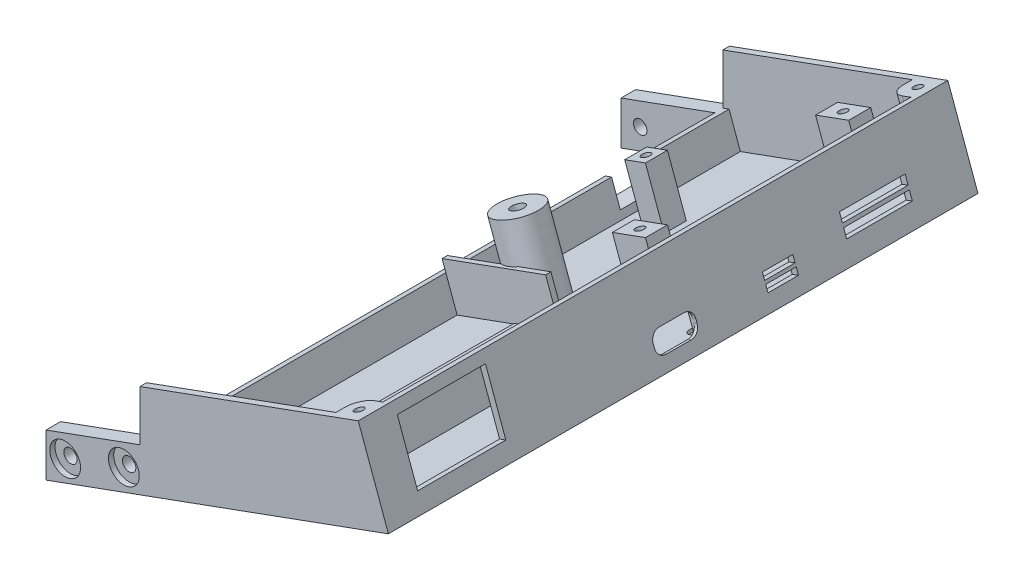
SolidWorks part; units mm, degrees
ref_plane "Front Plane" through (0, 0, 0) normal (0, 0, 1) x (1, 0, 0)
ref_plane "Top Plane" through (0, 0, 0) normal (0, 1, 0) x (1, 0, 0)
ref_plane "Right Plane" through (0, 0, 0) normal (1, 0, 0) x (0, 0, -1)
sketch "Sketch1" plane through (0, 0, 0) normal (0, 0, 1) x (1, 0, 0)
  line L1 (-6.3114, -55.8912) -> (15, -48.1345) construction
  line L2 (-6.1614, -45.8912) -> (-6.1614, -55.8912)
  line L3 (-6.1614, -45.8912) -> (-6.1614, -55.8912)
  line L4 (-6.3114, -55.8912) -> (15, -48.1345)
  line L6 (15, -48.1345) -> (15, -38.1345) construction
  line L7 (15.0513, -38.2754) -> (-6.2601, -46.0321)
  line L8 (15.0513, -38.2754) -> (-6.2601, -46.0321)
  line L9 (15, -48.1345) -> (15, -38.1345) construction
  line L10 (15, -48.1345) -> (15.141, -48.0832)
  line L11 (15.141, -48.0832) -> (15.141, -38.2428)
  line L12 (15.141, -38.2428) -> (15.0513, -38.2754)
  circle A0 centre (11.5, -44.4591) radius 1.525 construction
  circle A1 centre (11.5, -44.4591) radius 1.525
  circle A2 centre (-1.8114, -49.4969) radius 1.525 construction
  circle A3 centre (-1.8114, -49.4969) radius 1.525
  point P4 (90.4357, -10.8378)
  point P9 (16.5754, -48.1345)
  dimension "D3" = 0.15
  dimension "D1" = 0.15
  dimension "D2" = 0.15
extrude "Boss-Extrude1" add sketch "Sketch1" along normal blind 3.5 contours L9 L10 L11 L12 L8 | L4 L9 L8 L3 A3 A1
sketch "Sketch2" plane through (0, 0, 0) normal (0, 0, -1) x (-1, 0, 0)
  line L4 (6.1614, -45.9962) -> (-15.141, -38.2428)
  line L5 (-15.141, -38.2428) -> (-15.141, -48.0832)
  line L6 (-15.141, -48.0832) -> (6.1614, -55.8366)
  line L8 (6.1614, -45.9962) -> (-15.141, -38.2428)
  line L9 (-15.141, -38.2428) -> (-15.141, -48.0832)
  line L12 (-15.141, -48.0832) -> (6.1614, -55.8366)
  line L14 (6.1614, -55.8366) -> (6.1614, -45.9962)
  line L15 (6.1614, -55.8366) -> (6.1614, -45.9962)
  dimension "D1" = 0
extrude "Cut-Extrude1" cut sketch "Sketch2" against normal blind 0.2
ref_plane "Plane1" through (0, 0, -63.3801) normal (0, 0, 1) x (1, 0, 0)
mirror "Mirror2" about plane through (0, 0, -63.3801) normal (0, 0, 1) of bodies 102
sketch "Sketch3" plane through (0, 0, 3.5) normal (0, 0, 1) x (1, 0, 0)
  line L0 (15.141, -48.0832) -> (15.141, -38.2428) construction
  line L1 (15.141, -48.0832) -> (15.141, -38.2428)
  line L2 (15.141, -48.0832) -> (71.5225, -27.562)
  line L3 (71.5225, -27.562) -> (68.3599, -18.8727)
  line L4 (68.3599, -18.8727) -> (15.141, -38.2428)
  line L5 (15, -38.1345) -> (-6.3114, -45.8912) construction
  line L6 (-6.1614, -55.8366) -> (15.141, -48.0832) construction
  dimension "D1" = 60
extrude "Boss-Extrude2" add sketch "Sketch3" against normal up to surface (133.7602 mm away) up to face at (4.4898, -47.0397, -130.2602)
sketch "Sketch4" plane through (14.0622, -38.6354, 0) normal (-0.342, 0.9397, 0) x (0.9397, 0.342, 0)
  line L2 (56.2824, 130.2602) -> (56.2824, -3.5)
  line L3 (56.2824, 130.2602) -> (56.2824, -3.5)
  line L5 (57.7824, 128.7602) -> (-21.5215, 128.7602)
  line L6 (57.7824, 128.7602) -> (-21.5215, 128.7602)
  line L8 (57.7824, -2) -> (-21.5215, -2)
  line L9 (57.7824, -2) -> (-21.5215, -2)
  line L11 (2.648, 126.9602) -> (2.648, -0.2)
  line L12 (2.648, 128.7602) -> (2.648, -2)
  point P0 (2.6045, -2)
  dimension "D1" = 1.5
  dimension "D2" = 1.5
  dimension "D3" = 1.5
  dimension "D4" = 1.5
extrude "Cut-Extrude2" cut sketch "Sketch4" against normal blind 7.5 contours L6 L12 L9 L3
sketch "Sketch5" plane through (0, 0, 3.5) normal (0, 0, 1) x (1, 0, 0)
  line L1 (68.3599, -18.8727) -> (-6.1614, -45.9962) construction
  line L2 (15.15, 39.2) -> (15.15, -38.1345)
  line L3 (15.15, 39.2) -> (15.15, -74.4086)
  line L4 (68.3599, -18.8727) -> (-6.1614, -45.9962)
  line L5 (71.5225, -27.562) -> (68.3599, -18.8727) construction
  line L6 (71.5225, -27.562) -> (68.3599, -18.8727)
  line L7 (15.15, -26.7963) -> (64.6821, -8.7681)
  line L8 (64.6821, -8.7681) -> (68.3599, -18.8727)
  line L9 (-6.1614, -55.8366) -> (71.5225, -27.562) construction
  line M6 (68.3599, -18.8727) -> (-6.1614, -45.9962)
  dimension "D2" = 20
  dimension "D1" = 0.15
extrude "Boss-Extrude3" add sketch "Sketch5" against normal up to surface (1.5 mm away) contours L8 L7 L3 M6 up to face at (43.033, -32.0816, 2)
sketch "Sketch6" plane through (0, 0, -130.2602) normal (0, 0, -1) x (-1, 0, 0)
  line L0 (-15.15, -26.7963) -> (-64.6821, -8.7681) construction
  line L1 (-64.6821, -8.7681) -> (-68.3599, -18.8727) construction
  line L2 (-71.5225, -27.562) -> (-68.3599, -18.8727) construction
  line L3 (-68.3599, -18.8727) -> (6.1614, -45.9962) construction
  line L4 (-15.15, 39.2) -> (-15.15, -74.4086) construction
  line L5 (-15.15, -26.7963) -> (-64.6821, -8.7681)
  line L6 (-64.6821, -8.7681) -> (-68.3599, -18.8727)
  line L7 (-71.5225, -27.562) -> (-68.3599, -18.8727)
  line L8 (-68.3599, -18.8727) -> (6.1614, -45.9962)
  line L9 (-15.15, 39.2) -> (-15.15, -74.4086)
extrude "Boss-Extrude4" add sketch "Sketch6" against normal up to surface (1.5 mm away) contours L9 L5 L6 L8 up to face at (43.033, -32.0816, -128.7602)
sketch "Sketch7" plane through (54.2977, 19.7628, 0) normal (0.9397, 0.342, 0) x (0, 0, -1)
  line L0 (128.7602, -41.115) -> (-2, -41.115) construction
  line L1 (128.7602, -41.115) -> (-2, -41.115)
  line L2 (-2, -30.3619) -> (-2, -41.115) construction
  line L3 (-2, -30.3619) -> (-2, -41.115)
  line L4 (128.7602, -41.115) -> (128.7602, -30.3619) construction
  line L5 (128.7602, -41.115) -> (128.7602, -30.3619)
  line L6 (-2, -30.3619) -> (128.7602, -30.3619)
extrude "Boss-Extrude5" add sketch "Sketch7" against normal up to surface (1.5 mm away) up to face at (68.2329, -22.9096, -63.3801)
sketch "Sketch8" plane through (15.141, 0, 0) normal (-1, 0, 0) x (0, 0, 1)
  line L0 (-102.1, -43.2) -> (-113.1, -43.2) construction
  line L1 (-102.1, -43.2) -> (-113.1, -43.2)
  line L2 (-113.1, -52.7) -> (-113.1, -40.2) construction
  line L3 (-113.1, -52.7) -> (-113.1, -38.2428)
  line L4 (-102.1, -52.7) -> (-102.1, -40.2) construction
  line L5 (-102.1, -52.7) -> (-102.1, -38.2428)
  line L6 (-126.9602, -38.2428) -> (0.2, -38.2428) construction
  line L7 (-113.1, -38.2428) -> (-113.1, -35.0272)
  line L8 (-113.1, -35.0272) -> (-102.1, -35.0272)
  line L9 (-102.1, -35.0272) -> (-102.1, -38.2428)
  line M4 (0.2, -38.2428) -> (-126.9602, -38.2428)
extrude "Cut-Extrude3" cut sketch "Sketch8" against normal blind 5 contours L1 L5 L3 M4 | L9 L8 L7 M4
sketch "Sketch9" plane through (16.6273, -45.6831, 0) normal (-0.342, 0.9397, 0) x (0.9397, 0.342, 0)
  circle A0 centre (53.1824, 55.3801) radius 1.65 construction
  circle A1 centre (53.1824, 55.3801) radius 1.65
  circle A2 centre (53.1824, 71.3801) radius 1.65 construction
  circle A3 centre (53.1824, 71.3801) radius 1.65
extrude "Cut-Extrude4" cut sketch "Sketch9" against normal blind 1.8
sketch "Sketch10" plane through (16.6273, -45.6831, 0) normal (-0.342, 0.9397, 0) x (0.9397, 0.342, 0)
  line L2 (49.4824, 60.5301) -> (49.4824, 58.9301) construction
  line L5 (49.4824, 60.5301) -> (49.4824, 58.9301) construction
  line L6 (49.4824, 67.8301) -> (49.4824, 66.2301) construction
  line L7 (49.4824, 67.8301) -> (49.4824, 66.2301) construction
  line L8 (55.6824, 66.2301) -> (55.6824, 74.2801) construction
  line L9 (55.6824, 68.2301) -> (56.9824, 68.2301)
  line L10 (55.6824, 68.2301) -> (55.6824, 58.5301)
  line L11 (55.6824, 58.5301) -> (56.9824, 58.5301)
  line L12 (56.9824, 68.2301) -> (56.9824, 58.5301)
  dimension "D1" = 0.4
  dimension "D2" = 0.4
  dimension "D3" = 1.3
extrude "Cut-Extrude5" cut sketch "Sketch10" along normal blind 6
sketch "Sketch11" plane through (54.2977, 19.7628, 0) normal (0.9397, 0.342, 0) x (0, 0, -1)
  line L4 (66.2301, -43.415) -> (60.5301, -43.415)
  line L5 (60.5301, -47.415) -> (66.2301, -47.415)
  line L6 (66.2301, -43.415) -> (60.5301, -43.415)
  line L7 (60.5301, -47.415) -> (66.2301, -47.415)
  spline S0 degree 3 poles (60.5301, -43.415) (56.5301, -43.415) (56.5301, -47.415) (60.5301, -47.415) knots 0 0 0 0 1 1 1 1 weights 1 0.333333 0.333333 1
  spline S1 degree 3 poles (60.5301, -43.415) (56.5301, -43.415) (56.5301, -47.415) (60.5301, -47.415) knots 0 0 0 0 1 1 1 1 weights 1 0.333333 0.333333 1
  spline S2 degree 3 poles (66.2301, -47.415) (70.2301, -47.415) (70.2301, -43.415) (66.2301, -43.415) knots 0 0 0 0 1 1 1 1 weights 1 0.333333 0.333333 1
  spline S3 degree 3 poles (66.2301, -47.415) (70.2301, -47.415) (70.2301, -43.415) (66.2301, -43.415) knots 0 0 0 0 1 1 1 1 weights 1 0.333333 0.333333 1
  dimension "D1" = 0.4
extrude "Cut-Extrude6" cut sketch "Sketch11" against normal blind 6
sketch "Sketch12" plane through (54.2977, 19.7628, 0) normal (0.9397, 0.342, 0) x (0, 0, -1)
  line L8 (102.0602, -40.915) -> (102.0602, -42.915)
  line L9 (102.0602, -42.915) -> (116.9602, -42.915)
  line L10 (116.9602, -42.915) -> (116.9602, -40.915)
  line L11 (116.9602, -40.915) -> (102.0602, -40.915)
  line L12 (102.0602, -40.915) -> (102.0602, -42.915)
  line L13 (102.0602, -42.915) -> (116.9602, -42.915)
  line L14 (116.9602, -42.915) -> (116.9602, -40.915)
  line L15 (116.9602, -40.915) -> (102.0602, -40.915)
  line L20 (102.0602, -43.715) -> (102.0602, -45.715)
  line L21 (102.0602, -45.715) -> (116.9602, -45.715)
  line L22 (116.9602, -45.715) -> (116.9602, -43.715)
  line L23 (116.9602, -43.715) -> (102.0602, -43.715)
  line L24 (102.0602, -43.715) -> (102.0602, -45.715)
  line L25 (102.0602, -45.715) -> (116.9602, -45.715)
  line L26 (116.9602, -45.715) -> (116.9602, -43.715)
  line L27 (116.9602, -43.715) -> (102.0602, -43.715)
  line L32 (83.7602, -43.315) -> (83.7602, -44.815)
  line L33 (83.7602, -44.815) -> (90.6602, -44.815)
  line L34 (90.6602, -44.815) -> (90.6602, -43.315)
  line L35 (90.6602, -43.315) -> (83.7602, -43.315)
  line L36 (83.7602, -43.315) -> (83.7602, -44.815)
  line L37 (83.7602, -44.815) -> (90.6602, -44.815)
  line L38 (90.6602, -44.815) -> (90.6602, -43.315)
  line L39 (90.6602, -43.315) -> (83.7602, -43.315)
  line L44 (83.7602, -45.515) -> (83.7602, -47.015)
  line L45 (83.7602, -47.015) -> (90.6602, -47.015)
  line L46 (90.6602, -47.015) -> (90.6602, -45.515)
  line L47 (90.6602, -45.515) -> (83.7602, -45.515)
  line L48 (83.7602, -45.515) -> (83.7602, -47.015)
  line L49 (83.7602, -47.015) -> (90.6602, -47.015)
  line L50 (90.6602, -47.015) -> (90.6602, -45.515)
  line L51 (90.6602, -45.515) -> (83.7602, -45.515)
  dimension "D1" = 0.2
  dimension "D2" = 0.2
  dimension "D3" = 0.2
  dimension "D4" = 0.2
extrude "Cut-Extrude7" cut sketch "Sketch12" against normal blind 6
sketch "Sketch13" plane through (16.6273, -45.6831, 0) normal (-0.342, 0.9397, 0) x (0.9397, 0.342, 0)
  line L0 (15.1824, 81.6602) -> (56.2824, 81.6602) construction
  line L1 (31.7324, 81.6602) -> (39.7324, 81.6602)
  line L2 (31.7324, 81.6602) -> (31.7324, 76.6602)
  line L3 (31.7324, 76.6602) -> (39.7324, 76.6602)
  line L4 (39.7324, 81.6602) -> (39.7324, 76.6602)
  line L5 (56.2824, 122.7602) -> (15.1824, 122.7602) construction
  line L6 (31.7324, 122.7602) -> (39.7324, 122.7602)
  line L7 (31.7324, 122.7602) -> (31.7324, 127.7602)
  line L8 (31.7324, 127.7602) -> (39.7324, 127.7602)
  line L9 (39.7324, 122.7602) -> (39.7324, 127.7602)
  line L10 (15.1824, 122.7602) -> (15.1824, 81.6602) construction
  line L11 (15.1824, 99.7102) -> (10.1824, 99.7102)
  line L12 (15.1824, 99.7102) -> (15.1824, 104.7102)
  line L13 (15.1824, 104.7102) -> (10.1824, 104.7102)
  line L14 (10.1824, 99.7102) -> (10.1824, 104.7102)
  line L15 (35.7324, 81.6602) -> (35.7324, 122.7602) construction
  line L16 (15.1824, 102.2102) -> (35.7324, 102.2102) construction
  point P22 (44.4493, 122.7602)
  point P23 (35.7324, 122.7602)
  point P24 (25.1388, 102.2102)
  dimension "D1" = 5
  dimension "D2" = 5
  dimension "D3" = 8
  dimension "D4" = 5
extrude "Boss-Extrude6" add sketch "Sketch13" along normal up to surface (12.5 mm away)
sketch "Sketch14" plane through (12.3521, -33.937, 0) normal (-0.342, 0.9397, 0) x (0.9397, 0.342, 0)
  line L0 (35.7324, 76.6602) -> (35.7324, 81.6602) construction
  line L1 (31.7324, 76.6602) -> (39.7324, 76.6602) construction
  line L2 (31.7324, 81.6602) -> (39.7324, 81.6602) construction
  line L3 (35.7324, 122.7602) -> (35.7324, 127.7602) construction
  line L4 (39.7324, 122.7602) -> (31.7324, 122.7602) construction
  line L5 (31.7324, 127.7602) -> (39.7324, 127.7602) construction
  line L6 (10.1824, 102.2102) -> (15.1824, 102.2102) construction
  line L7 (10.1824, 99.7102) -> (10.1824, 104.7102) construction
  line L8 (15.1824, 104.7102) -> (15.1824, 99.7102) construction
  circle A0 centre (35.7324, 79.1602) radius 1
  circle A1 centre (12.6824, 102.2102) radius 1
  circle A2 centre (35.7324, 125.2602) radius 1
  dimension "D1" = 2
  dimension "D2" = 2
  dimension "D3" = 2
extrude "Cut-Extrude8" cut sketch "Sketch14" against normal blind 10
sketch "Sketch15" plane through (16.6273, -45.6831, 0) normal (-0.342, 0.9397, 0) x (0.9397, 0.342, 0)
  line L0 (56.2824, -2) -> (2.648, -2) construction
  line L1 (37.648, -2) -> (38.848, -2)
  line L2 (37.648, -2) -> (37.648, 48)
  line L3 (37.648, 48) -> (38.848, 48)
  line L4 (38.848, -2) -> (38.848, 48)
  line L5 (2.648, 128.7602) -> (2.648, -2) construction
  line L6 (2.648, 64.5) -> (27.648, 64.5)
  line L7 (2.648, 64.5) -> (2.648, 65.7)
  line L8 (2.648, 65.7) -> (27.648, 65.7)
  line L9 (27.648, 64.5) -> (27.648, 65.7)
  line L10 (36.648, -2) -> (36.648, 61.5) construction
  line L11 (2.648, 63.5) -> (38.648, 63.5) construction
  dimension "D1" = 1
  dimension "D2" = 1
  dimension "D3" = 1.2
  dimension "D4" = 1.2
  dimension "D5" = 25
  dimension "D6" = 50
extrude "Boss-Extrude7" add sketch "Sketch15" along normal blind 10
sketch "Sketch16" plane through (54.2977, 19.7628, 0) normal (0.9397, 0.342, 0) x (0, 0, -1)
  line L0 (4.5, -39.6119) -> (-3.5, -39.6119) construction
  line L1 (4.5, -32.8619) -> (24.5, -32.8619)
  line L2 (4.5, -32.8619) -> (4.5, -46.3619)
  line L3 (4.5, -46.3619) -> (24.5, -46.3619)
  line L4 (24.5, -32.8619) -> (24.5, -46.3619)
  line L5 (130.2602, -30.3619) -> (-3.5, -30.3619) construction
  line L6 (-3.5, -50.3619) -> (-3.5, -30.3619) construction
  point P9 (8.689, -46.3619)
  point P10 (0, 0)
  dimension "D1" = 13.5
  dimension "D2" = 20
  dimension "D3" = 8
  dimension "D4" = 2.5
extrude "Cut-Extrude9" cut sketch "Sketch16" against normal blind 10
sketch "Sketch17" plane through (16.6273, -45.6831, 0) normal (-0.342, 0.9397, 0) x (0.9397, 0.342, 0)
  line L0 (5.0715, -3.5) -> (57.7824, -3.5) construction
  line L1 (57.7824, 130.2602) -> (57.7824, -3.5) construction
  line L2 (50.7824, 0) -> (50.7824, -3.5)
  line L3 (50.7824, -3.5) -> (57.7824, -3.5)
  line L4 (57.7824, -3.5) -> (57.7824, 3.5)
  line L5 (57.7824, 3.5) -> (54.2824, 3.5)
  line L6 (57.7824, 63.3801) -> (-9.4136, 63.3801) construction
  line L7 (57.7824, 123.2602) -> (54.2824, 123.2602)
  line L8 (57.7824, 130.2602) -> (57.7824, 123.2602)
  line L9 (50.7824, 130.2602) -> (57.7824, 130.2602)
  line L10 (50.7824, 126.7602) -> (50.7824, 130.2602)
  circle A0 centre (54.2824, 0) radius 3.5
  circle A1 centre (54.2824, 126.7602) radius 3.5
  line M23 (38.848, -2) -> (56.2824, -2)
  line M24 (56.2824, -2) -> (56.2824, 58.5301)
  line M28 (56.2824, 68.2301) -> (56.2824, 128.7602)
  line M29 (56.2824, 128.7602) -> (2.648, 128.7602)
  dimension "D1" = 7
extrude "Boss-Extrude8" add sketch "Sketch17" along normal up to surface (18.2531 mm away) contours L8 A1 L7 M28 | A1 M28 M29 | A1 L7 M28 | A1 M29 M28 | L9 A1 L8 | A1 L9 L10 M29 | L10 A1 M29 | A0 L4 L5 M24 | A0 L5 M24 | A0 M23 M24 | A0 L3 L4 | A0 M23 M24 | A0 L2 L3 M23 | A0 L2 M23 up to face at (39.5637, -17.9105, -63.3801)
sketch "Sketch18" plane through (10.3844, -28.5309, 0) normal (-0.342, 0.9397, 0) x (0.9397, 0.342, 0)
  circle A0 centre (54.2824, 0) radius 1
  circle A1 centre (54.2824, 126.7602) radius 1
  dimension "D1" = 2
  dimension "D2" = 2
extrude "Cut-Extrude10" cut sketch "Sketch18" against normal through all
sketch "Sketch19" plane through (16.6273, -45.6831, 0) normal (-0.342, 0.9397, 0) x (0.9397, 0.342, 0)
  line L1 (40.6112, 26.6776) -> (58.6112, 26.6776)
  line L2 (40.6112, 26.6776) -> (40.6112, 51.6776)
  line L3 (40.6112, 51.6776) -> (58.6112, 51.6776)
  line L4 (58.6112, 26.6776) -> (58.6112, 51.6776)
  line L5 (40.6112, 26.6776) -> (58.6112, 51.6776) construction
  line L6 (40.6112, 51.6776) -> (58.6112, 26.6776) construction
  point P0 (49.6112, 39.1776)
  point P5 (52.937, 34.818)
  point P6 (54.0217, 38.2781)
  point P7 (49.6112, 39.1776)
  dimension "D1" = 25
  dimension "D2" = 18
sketch "Sketch20" plane through (0, 0, 3.5) normal (0, 0, 1) x (1, 0, 0)
  circle A0 centre (11.5, -44.4591) radius 3.5
  circle A1 centre (-1.8114, -49.4969) radius 3.5
  dimension "D1" = 7
  dimension "D2" = 7
extrude "Cut-Extrude11" cut sketch "Sketch20" against normal blind 1.2
sketch "Sketch21" plane through (0, 0, -130.2602) normal (0, 0, -1) x (-1, 0, 0)
  circle A0 centre (1.8114, -49.4969) radius 3.5 construction
  circle A1 centre (-11.5, -44.4591) radius 3.5 construction
  circle A2 centre (1.8114, -49.4969) radius 3.5
  circle A3 centre (-11.5, -44.4591) radius 3.5
extrude "Cut-Extrude12" cut sketch "Sketch21" against normal blind 1.2
sketch "Sketch22" plane through (17.2248, -47.3247, 0) normal (0.342, -0.9397, 0) x (0.9397, 0.342, 0)
  circle A2 centre (53.1824, -55.3801) radius 3.5
  circle A3 centre (53.1824, -55.3801) radius 3.5
  circle A6 centre (53.1824, -71.3801) radius 3.5
  circle A7 centre (53.1824, -71.3801) radius 3.5
  dimension "D2" = 7
  dimension "D3" = 1.85
  dimension "D1" = 1.85
extrude "Cut-Extrude13" cut sketch "Sketch22" against normal blind 0.8
sketch "Sketch23" plane through (17.2248, -47.3247, 0) normal (0.342, -0.9397, 0) x (0.9397, 0.342, 0)
  circle A0 centre (54.2824, -126.7602) radius 2.75
  circle A1 centre (54.2824, 0) radius 2.75
  dimension "D1" = 5.5
  dimension "D2" = 5.5
extrude "Cut-Extrude14" cut sketch "Sketch23" against normal blind 0.8
sketch "Sketch24" plane through (16.9512, -46.573, 0) normal (0.342, -0.9397, 0) x (0.9397, 0.342, 0)
  circle A0 centre (53.1824, -55.3801) radius 1.65 construction
  circle A1 centre (53.1824, -55.3801) radius 1.65
  circle A2 centre (53.1824, -71.3801) radius 1.65 construction
  circle A3 centre (53.1824, -71.3801) radius 1.65
  circle A4 centre (54.2824, 0) radius 1 construction
  circle A5 centre (54.2824, 0) radius 1
  circle A6 centre (54.2824, -126.7602) radius 1 construction
  circle A7 centre (54.2824, -126.7602) radius 1
extrude "Boss-Extrude9" add sketch "Sketch24" against normal blind 0.3
sketch "Sketch25" plane through (54.2977, 19.7628, 0) normal (0.9397, 0.342, 0) x (0, 0, -1)
  line L0 (58.5301, -45.415) -> (58.5301, -44.615)
  line L1 (68.2301, -45.415) -> (68.2301, -44.615)
  line L2 (68.2301, -44.615) -> (58.5301, -44.615) construction
  line L3 (60.5301, -44.615) -> (66.2301, -44.615) construction
  line L4 (60.5301, -42.615) -> (66.2301, -42.615)
  line L5 (60.5301, -46.615) -> (66.2301, -46.615)
  line L7 (66.2301, -43.415) -> (60.5301, -43.415) construction
  line L8 (60.5301, -47.415) -> (66.2301, -47.415) construction
  line L9 (60.5301, -47.415) -> (66.2301, -47.415)
  arc A0 (60.5301, -43.415) -> (60.5301, -47.415) centre (60.5301, -45.415) ccw construction
  arc A1 (66.2301, -47.415) -> (66.2301, -43.415) centre (66.2301, -45.415) ccw construction
  arc A2 (60.5301, -42.615) -> (60.5301, -46.615) centre (60.5301, -44.615) ccw
  arc A3 (66.2301, -46.615) -> (66.2301, -42.615) centre (66.2301, -44.615) ccw
  arc A4 (66.2301, -47.415) -> (66.2301, -43.415) centre (66.2301, -45.415) ccw
  arc A5 (60.5301, -43.415) -> (60.5301, -47.415) centre (60.5301, -45.415) ccw
  point P12 (63.3801, -44.615)
  point P17 (63.3801, -44.8557)
  point P20 (60.7127, -44.615)
  spline M32 degree 3 poles (60.5301, -47.415) (56.5301, -47.415) (56.5301, -43.415) (60.5301, -43.415) knots 0 0 0 0 1 1 1 1 weights 1 0.333333 0.333333 1
  line M33 (60.5301, -43.415) -> (66.2301, -43.415)
  spline M34 degree 3 poles (66.2301, -43.415) (70.2301, -43.415) (70.2301, -47.415) (66.2301, -47.415) knots 0 0 0 0 1 1 1 1 weights 1 0.333333 0.333333 1
  dimension "D1" = 1.2
  dimension "D2" = 0.8
extrude "Cut-Extrude15" cut sketch "Sketch25" against normal blind 3.3 contours A3 L4 A2 M34 M32 M33 | A2 L0 M32 | A3 L1 M34
sketch "Sketch26" plane through (16.6273, -45.6831, 0) normal (-0.342, 0.9397, 0) x (0.9397, 0.342, 0)
  line L0 (5.0715, 130.2602) -> (57.7824, 130.2602) construction
  line L1 (57.7824, 130.2602) -> (57.7824, -3.5) construction
  circle A0 centre (17.7824, 70.2602) radius 5
  circle A1 centre (17.7824, 70.2602) radius 1.5
  dimension "D1" = 3
  dimension "D2" = 10
  dimension "D3" = 60
  dimension "D4" = 40
extrude "Boss-Extrude10" add sketch "Sketch26" along normal up to surface (18.2531 mm away) up to face at (60.4535, -10.3072, 0)
